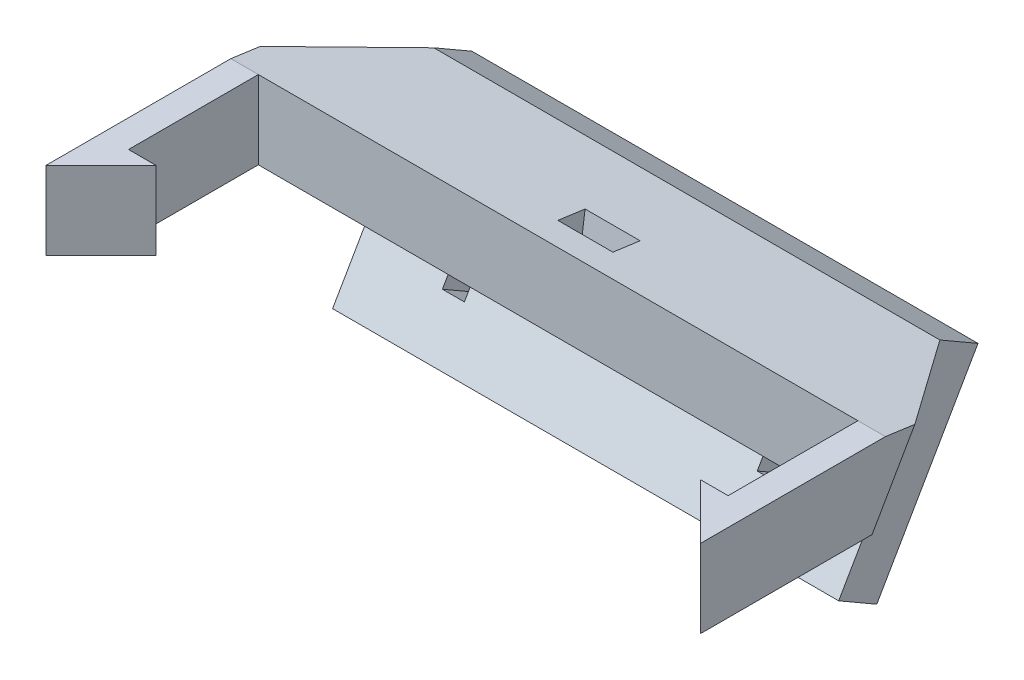
SolidWorks part; units mm, degrees
ref_plane "Front Plane" through (0, 0, 0) normal (0, 0, 1) x (1, 0, 0)
ref_plane "Top Plane" through (0, 0, 0) normal (0, 1, 0) x (1, 0, 0)
ref_plane "Right Plane" through (0, 0, 0) normal (1, 0, 0) x (0, 0, -1)
sketch "Sketch1" plane through (0, 0, 0) normal (0, 0, 1) x (1, 0, 0)
  line L1 (-37.7825, 17.78) -> (37.7825, 17.78)
  line L2 (-37.7825, 17.78) -> (-37.7825, -17.78)
  line L3 (-37.7825, -17.78) -> (37.7825, -17.78)
  line L4 (37.7825, 17.78) -> (37.7825, -17.78)
  point P4 (0, 17.78)
  point P6 (-37.7825, 0)
  dimension "D1" = 75.565
extrude "Boss-Extrude1" add sketch "Sketch1" against normal blind 3.175
sketch "Sketch5" plane through (0, 0, 0) normal (0, 0, 1) x (1, 0, 0)
  line L1 (-6.35, 17.78) -> (6.35, 17.78)
  line L2 (-6.35, 17.78) -> (-6.35, 14.605)
  line L3 (-6.35, 14.605) -> (6.35, 14.605)
  line L4 (6.35, 17.78) -> (6.35, 14.605)
  line L5 (-6.35, -14.605) -> (6.35, -14.605)
  line L6 (-6.35, -14.605) -> (-6.35, -17.78)
  line L7 (-6.35, -17.78) -> (6.35, -17.78)
  line L8 (6.35, -14.605) -> (6.35, -17.78)
  line L10 (37.7825, 17.78) -> (-37.7825, 17.78) construction
  point P8 (0, 17.78)
  point P9 (0, -17.78)
  dimension "D1" = 3.175
  dimension "D2" = 3.175
  dimension "D3" = 29.21
  dimension "D4" = 12.7
extrude "Boss-Extrude3" add sketch "Sketch5" along normal blind 14.986
sketch "Sketch6" plane through (0, 0, 0) normal (0, 0, 1) x (1, 0, 0)
  line L0 (-37.7825, 17.78) -> (-37.7825, -17.78) construction
  line L1 (-37.7825, 4.5142) -> (-34.6075, 4.5142)
  line L2 (-37.7825, 4.5142) -> (-37.7825, -4.5142)
  line L3 (-37.7825, -4.5142) -> (-34.6075, -4.5142)
  line L4 (-34.6075, 4.5142) -> (-34.6075, -4.5142)
  line L5 (37.7825, -17.78) -> (37.7825, 17.78) construction
  line L6 (37.7825, 4.5142) -> (34.6075, 4.5142)
  line L7 (37.7825, 4.5142) -> (37.7825, -4.5142)
  line L8 (37.7825, -4.5142) -> (34.6075, -4.5142)
  line L9 (34.6075, 4.5142) -> (34.6075, -4.5142)
  point P12 (37.7825, 0)
  point P14 (-37.7825, 0)
  dimension "D1" = 3.175
  dimension "D2" = 3.175
  dimension "D3" = 69.215
extrude "Boss-Extrude4" add sketch "Sketch6" along normal blind 14.986
sketch "Sketch7" plane through (-6.35, 0, 0) normal (-1, 0, 0) x (0, 0, 1)
  line L0 (14.986, -17.78) -> (14.986, -11.43)
  line L1 (14.986, -11.43) -> (21.336, -17.78)
  line L2 (21.336, -17.78) -> (14.986, -17.78)
  line L3 (14.986, 17.78) -> (14.986, 11.43)
  line L4 (14.986, 11.43) -> (21.336, 17.78)
  line L5 (21.336, 17.78) -> (14.986, 17.78)
  dimension "D1" = 6.35
  dimension "D2" = 6.35
  dimension "D3" = 6.35
  dimension "D4" = 6.35
extrude "Boss-Extrude5" add sketch "Sketch7" against normal up to surface (12.7 mm away) up to face at (6.35, 16.1925, 7.493)
sketch "Sketch8" plane through (0, -4.5142, 0) normal (0, -1, 0) x (1, 0, 0)
  line L0 (-37.7825, 14.986) -> (-31.4325, 14.986)
  line L1 (-31.4325, 14.986) -> (-37.7825, 21.336)
  line L2 (-37.7825, 21.336) -> (-37.7825, 14.986)
  line L3 (37.7825, 14.986) -> (31.4325, 14.986)
  line L4 (31.4325, 14.986) -> (37.7825, 21.336)
  line L5 (37.7825, 21.336) -> (37.7825, 14.986)
  dimension "D1" = 6.35
  dimension "D2" = 6.35
  dimension "D3" = 6.35
  dimension "D4" = 6.35
extrude "Boss-Extrude6" add sketch "Sketch8" against normal up to surface (9.0284 mm away) up to face at (-36.195, 4.5142, 7.493)
sketch "Sketch9" plane through (-37.7825, 0, 0) normal (-1, 0, 0) x (0, 0, 1)
  line L0 (-3.175, 17.78) -> (-18.5729, 8.89)
  line L1 (-18.5729, 8.89) -> (-3.175, -17.78)
  line L3 (-3.175, 17.78) -> (-3.175, -17.78) construction
  line L12 (0, 4.5142) -> (0, 17.78)
  line L13 (0, 17.78) -> (-3.175, 17.78)
  line L14 (-3.175, 17.78) -> (-3.175, -17.78)
  line L15 (-3.175, -17.78) -> (0, -17.78)
  line L16 (0, -17.78) -> (0, -4.5142)
  line L17 (0, -4.5142) -> (21.336, -4.5142)
  line L18 (21.336, -4.5142) -> (21.336, 4.5142)
  line L19 (21.336, 4.5142) -> (0, 4.5142)
  line L22 (-3.175, 17.78) -> (-3.175, -17.78)
  dimension "D1" = 90
  dimension "D2" = 30
  dimension "D3" = 0
extrude "Boss-Extrude7" add sketch "Sketch9" against normal up to surface (75.565 mm away) up to face at (37.7825, 0, 4.5403)
sketch "Sketch10" plane through (0, -5.8198, -10.0802) normal (0, -0.5, -0.866) x (-1, 0, 0)
  line L0 (37.7825, 16.9854) -> (37.7825, -13.8104) construction
  line L1 (-37.7825, -13.8104) -> (37.7825, -13.8104)
  line L2 (-37.7825, -13.8104) -> (-37.7825, 9.5576)
  line L3 (-37.7825, 9.5576) -> (37.7825, 9.5576)
  line L4 (37.7825, -13.8104) -> (37.7825, 9.5576)
  dimension "D1" = 23.368
extrude "Boss-Extrude8" add sketch "Sketch10" along normal blind 5.08
sketch "Sketch11" plane through (-37.7825, 0, 0) normal (-1, 0, 0) x (0, 0, 1)
  line L0 (-14.859, 2.4573) -> (0, 4.5142)
  line L1 (0, 4.5142) -> (36.8887, 18.2755)
  line L2 (36.8887, 18.2755) -> (5.2861, 25.1503)
  line L3 (5.2861, 25.1503) -> (-30.3838, 8.2332)
  line L4 (-30.3838, 8.2332) -> (-14.859, 2.4573)
  line L5 (-3.175, -17.78) -> (-8.1255, -9.2055)
  line L6 (-8.1255, -9.2055) -> (0, -4.5142)
  line L7 (0, -4.5142) -> (40.1585, -20.4064)
  line L8 (40.1585, -20.4064) -> (15.5997, -25.3949)
  line L9 (15.5997, -25.3949) -> (-3.175, -17.78)
  line L10 (-7.5744, -20.32) -> (-19.2584, -0.0827) construction
  line L11 (-7.5744, -20.32) -> (-3.175, -17.78) construction
  point P16 (-8.3025, -8.8989)
  point P17 (-9.5426, -6.751)
extrude "Cut-Extrude1" cut sketch "Sketch11" against normal through all
sketch "Sketch12" plane through (0, 4.4293, -0.6131) normal (0, 0.9906, -0.1371) x (1, 0, 0)
  line L0 (34.6075, -0.619) -> (-34.6075, -0.619) construction
  line L1 (-3.175, 5.731) -> (3.175, 5.731)
  line L2 (-3.175, 5.731) -> (-3.175, 2.556)
  line L3 (-3.175, 2.556) -> (3.175, 2.556)
  line L4 (3.175, 5.731) -> (3.175, 2.556)
  point P6 (0, 2.556)
  point P7 (0, -0.619)
  dimension "D1" = 3.175
  dimension "D2" = 6.35
  dimension "D3" = 3.175
extrude "Cut-Extrude2" cut sketch "Sketch12" against normal up to next and the other way through all
sketch "Sketch13" plane through (0, 8.2771, -4.7788) normal (0, 0.866, -0.5) x (1, 0, 0)
  line L0 (0, 11.6396) -> (0, 16.7196) construction
  line L1 (-37.7825, 11.6396) -> (37.7825, 11.6396) construction
  line L2 (-37.7825, 16.7196) -> (37.7825, 16.7196) construction
  line L3 (-29.21, 11.6396) -> (-37.7825, 0.9179)
  line L4 (-37.7825, 16.7196) -> (-29.21, 16.7196)
  line L5 (-37.7825, 16.7196) -> (-37.7825, 11.6396)
  line L6 (37.7825, 0.9179) -> (37.7825, 11.6396)
  line L7 (-29.21, 16.7196) -> (-29.21, 11.6396)
  line L8 (-37.7825, 0.9179) -> (-37.7825, 11.6396)
  line L9 (37.7825, 16.7196) -> (37.7825, 11.6396)
  line L10 (37.7825, 16.7196) -> (29.21, 16.7196)
  line L11 (29.21, 11.6396) -> (37.7825, 0.9179)
  line L12 (29.21, 16.7196) -> (29.21, 11.6396)
  line L13 (-37.7825, 11.6396) -> (-37.7825, -2.2571) construction
  point P18 (-37.7825, -2.2571)
  point P19 (0, 0)
  point P20 (0, 0)
  point P21 (-37.7825, 0.6705)
  dimension "D1" = 29.21
  dimension "D2" = 3.175
extrude "Cut-Extrude3" cut sketch "Sketch13" against normal through all
sketch "Sketch14" plane through (0, -8.3598, -14.4796) normal (0, -0.5, -0.866) x (-1, 0, 0)
  line L0 (-29.21, -3.9395) -> (29.4553, -3.9395) construction
  line L1 (-29.21, -13.8104) -> (-29.21, 9.5576) construction
  line L2 (0.1227, -3.9395) -> (0.1227, -13.8104) construction
  line L3 (-19.3205, -3.9395) -> (-16.7805, -3.9395)
  line L4 (-19.3205, -3.9395) -> (-19.3205, -7.7495)
  line L5 (-19.3205, -7.7495) -> (-16.7805, -7.7495)
  line L6 (-16.7805, -3.9395) -> (-16.7805, -7.7495)
  line L7 (-29.21, -13.8104) -> (29.21, -13.8104) construction
  line L8 (19.5659, -3.9395) -> (17.0259, -3.9395)
  line L9 (17.0259, -3.9395) -> (17.0259, -7.7495)
  line L10 (19.5659, -7.7495) -> (17.0259, -7.7495)
  line L11 (19.5659, -3.9395) -> (19.5659, -7.7495)
  point P16 (-29.21, -3.7081)
  dimension "D1" = 2.54
  dimension "D2" = 3.81
extrude "Cut-Extrude4" cut sketch "Sketch14" against normal up to next
